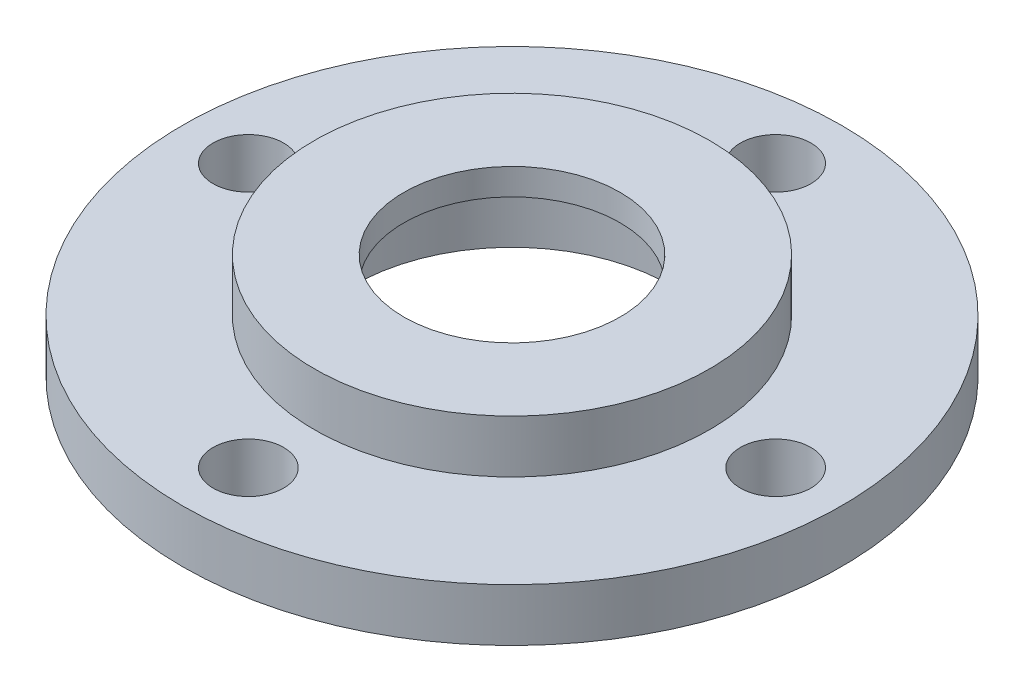
SolidWorks part; units mm, degrees
ref_plane "Front Plane" through (0, 0, 0) normal (0, 0, 1) x (1, 0, 0)
ref_plane "Top Plane" through (0, 0, 0) normal (0, 1, 0) x (1, 0, 0)
ref_plane "Right Plane" through (0, 0, 0) normal (1, 0, 0) x (0, 0, -1)
sketch "Sketch1" plane through (0, 0, 0) normal (0, 1, 0) x (1, 0, 0)
  circle A0 centre (0, 0) radius 15.875
  dimension "D1" = 31.75
extrude "Boss-Extrude1" add sketch "Sketch1" along normal blind 2.54
sketch "Sketch2" plane through (0, 2.54, 0) normal (0, 1, 0) x (1, 0, 0)
  circle A0 centre (0, 0) radius 9.525
  dimension "D1" = 19.05
extrude "Boss-Extrude2" add sketch "Sketch2" along normal blind 2.54
sketch "Sketch3" plane through (0, 0, 0) normal (0, -1, 0) x (1, 0, 0)
  circle A0 centre (0, 0) radius 7.62
  dimension "D1" = 15.24
extrude "Cut-Extrude1" cut sketch "Sketch3" against normal blind 3.81
sketch "Sketch4" plane through (0, 5.08, 0) normal (0, 1, 0) x (1, 0, 0)
  circle A0 centre (0, 0) radius 5.207
  dimension "D1" = 10.414
extrude "Cut-Extrude2" cut sketch "Sketch4" against normal up to next
sketch "Sketch5" plane through (0, 2.54, 0) normal (0, 1, 0) x (1, 0, 0)
  line L0 (0, 15.875) -> (0, 0) construction
  circle A0 centre (0, 12.7) radius 1.7
  circle A1 centre (0, 0) radius 15.875 construction
  circle A2 centre (12.7, 0) radius 1.7
  circle A3 centre (0, -12.7) radius 1.7
  circle A4 centre (-12.7, 0) radius 1.7
  point P18 (0, 0)
  dimension "D2" = 3.4
  dimension "D1" = 12.7
  dimension "D3" = 4
extrude "Cut-Extrude3" cut sketch "Sketch5" against normal up to next
move or copy body "Body-Move/Copy1" bodies to move or copy 106 parameters "D1"=0, "D2"=0, "D3"=0
